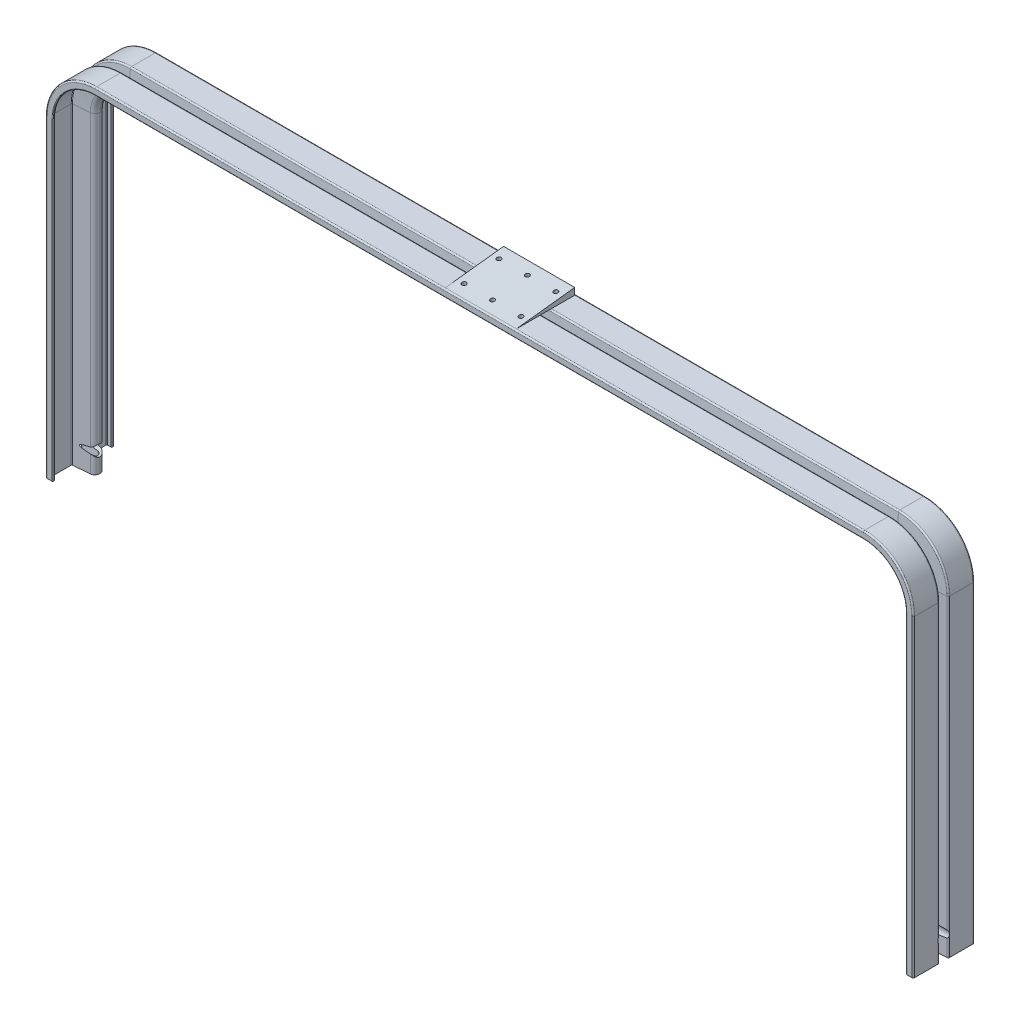
SolidWorks part; units mm, degrees
material "AISI 1020 Acero laminado en frío"
ref_plane "Alzado" through (0, 0, 0) normal (0, 0, 1) x (1, 0, 0)
ref_plane "Planta" through (0, 0, 0) normal (0, 1, 0) x (1, 0, 0)
ref_plane "Vista lateral" through (0, 0, 0) normal (1, 0, 0) x (0, 0, -1)
other "Tabla de configuración"
sketch "Croquis2" plane through (0, 0, 0) normal (1, 0, 0) x (0, 0, -1)
  line L4 (2, -2) -> (-2, -2) construction
  line L5 (21.5, 12) -> (-21.5, 12) construction
  line L8 (-3.5977, -0.2791) -> (-2.1024, -0.1595) construction
  line L9 (0, -3.5) -> (0, 12) construction
  line L10 (-3.0048, 11.1196) -> (-2.9952, 11)
  line L11 (-5.8278, 10.3021) -> (-7.826, 10.3021) construction
  line L12 (-5.8278, 10.3021) -> (-5.8278, 13.2411) construction
  line L13 (-5.8278, 13.2411) -> (-20.5, 13.2411)
  line L14 (-21.5, 12.2411) -> (-21.5, 8.7411)
  line L15 (-21, 8.2411) -> (-20.5, 8.2411)
  line L16 (-20, 8.7411) -> (-20, 11.2411)
  line L17 (-19.5, 11.7411) -> (-5.8278, 11.7411)
  line L18 (-4.5, 11) -> (-4.9298, 10.9656) construction
  line L19 (-4.5, 11) -> (-4.5881, 12.1007) construction
  line L20 (-5.8278, 11.7411) -> (-4.3336, 11.7411) construction
  line L21 (-4.5, 11) -> (-4.5225, 11.281)
  line L22 (-5.0209, 11.7411) -> (-5.8278, 11.7411)
  line L23 (-2.9952, 11) -> (-3.0048, 11.1196)
  line L24 (-3.0048, 11.1196) -> (-3.1009, 12.3209)
  line L25 (-5.8278, 13.2411) -> (-4.0977, 13.2411)
  line L26 (0.1088, -3.5) -> (-0.1088, -3.5)
  line L27 (-3.5977, -0.2791) -> (-4.5, 11)
  line L28 (-1.2335, -2) -> (-1.103, -2.2764) construction
  line L29 (-2.5488, 5.4203) -> (-1.7472, -4.6) construction
  line L30 (-1.236, -2) -> (-1.2335, -2)
  line L31 (-2.1024, -0.1595) -> (-2.9952, 11)
  line L32 (0.1088, -2) -> (-0.1088, -2)
  line L33 (-2.1024, -0.1595) -> (-2.9952, 11)
  line L34 (2.5488, 5.4203) -> (1.7472, -4.6) construction
  line L35 (1.2335, -2) -> (1.103, -2.2764) construction
  line L36 (5.8278, 11.7411) -> (4.3336, 11.7411) construction
  line L37 (4.5, 11) -> (4.5881, 12.1007) construction
  line L38 (4.5, 11) -> (4.9298, 10.9656) construction
  line L39 (5.8278, 10.3021) -> (5.8278, 13.2411) construction
  line L40 (5.8278, 10.3021) -> (7.826, 10.3021) construction
  line L41 (3.5977, -0.2791) -> (2.1024, -0.1595) construction
  line L42 (2.1024, -0.1595) -> (2.9952, 11)
  line L43 (2.1024, -0.1595) -> (2.9952, 11)
  line L44 (1.236, -2) -> (1.2335, -2)
  line L45 (3.5977, -0.2791) -> (4.5, 11)
  line L46 (5.8278, 13.2411) -> (4.0977, 13.2411)
  line L47 (3.0048, 11.1196) -> (3.1009, 12.3209)
  line L48 (2.9952, 11) -> (3.0048, 11.1196)
  line L49 (5.0209, 11.7411) -> (5.8278, 11.7411)
  line L50 (4.5, 11) -> (4.5225, 11.281)
  line L51 (19.5, 11.7411) -> (5.8278, 11.7411)
  line L52 (20, 8.7411) -> (20, 11.2411)
  line L53 (21, 8.2411) -> (20.5, 8.2411)
  line L54 (21.5, 12.2411) -> (21.5, 8.7411)
  line L55 (5.8278, 13.2411) -> (20.5, 13.2411)
  line L56 (3.0048, 11.1196) -> (2.9952, 11)
  arc A0 (-2.1024, -0.1595) -> (-0.1088, -2) centre (-0.1088, 0) ccw
  arc A1 (3.5977, -0.2791) -> (0.1088, -3.5) centre (0.1088, 0) cw
  arc A4 (-5.0209, 11.7411) -> (-4.5225, 11.281) centre (-5.0209, 11.2411) cw
  arc A5 (-3.1009, 12.3209) -> (-4.0977, 13.2411) centre (-4.0977, 12.2411) ccw
  arc A6 (-20, 11.2411) -> (-19.5, 11.7411) centre (-19.5, 11.2411) cw
  arc A7 (-20.5, 13.2411) -> (-21.5, 12.2411) centre (-20.5, 12.2411) ccw
  arc A8 (-20, 8.7411) -> (-20.5, 8.2411) centre (-20.5, 8.7411) cw
  arc A9 (-21, 8.2411) -> (-21.5, 8.7411) centre (-21, 8.7411) cw
  arc A10 (-3.5977, -0.2791) -> (-0.1088, -3.5) centre (-0.1088, 0) ccw
  arc A11 (21, 8.2411) -> (21.5, 8.7411) centre (21, 8.7411) ccw
  arc A12 (20, 8.7411) -> (20.5, 8.2411) centre (20.5, 8.7411) ccw
  arc A13 (20.5, 13.2411) -> (21.5, 12.2411) centre (20.5, 12.2411) cw
  arc A14 (20, 11.2411) -> (19.5, 11.7411) centre (19.5, 11.2411) ccw
  arc A15 (3.1009, 12.3209) -> (4.0977, 13.2411) centre (4.0977, 12.2411) cw
  arc A16 (5.0209, 11.7411) -> (4.5225, 11.281) centre (5.0209, 11.2411) ccw
  arc A17 (2.1024, -0.1595) -> (0.1088, -2) centre (0.1088, 0) cw
  point P4 (0, 0)
  point P8 (0, 12)
  point P32 (-4.5593, 11.7411)
  point P49 (-1.9552, -2)
  point P88 (0, -2)
  point P90 (1.9552, -2)
  point P91 (4.5593, 11.7411)
  dimension "D3" = 3.5
  dimension "D8" = 1.5
  dimension "D9" = 0.5
  dimension "D11" = 1
  dimension "D12" = 1.361
  dimension "D13" = 0.5
  dimension "D14" = 1
  dimension "D15" = 0.5
  dimension "D5" = 2
  dimension "D6" = 2
  dimension "D10" = 1.5
  dimension "D16" = 21.5
extrude "Saliente-Extruir1" add sketch "Croquis2" along normal mid plane 540
sketch "Croquis4" plane through (0, 0, 0) normal (0, 0, 1) x (1, 0, 0)
  line L0 (0, -4.7328) -> (0, 13.2411) construction
  line L1 (270, 13.2411) -> (-270, 13.2411) construction
  line L2 (0, 115.1283) -> (-251.0425, 15.746)
  line L3 (-270, -12.1478) -> (-270, -232.1463)
  line L4 (270, -12.1478) -> (270, -232.1463)
  line L5 (0, 115.1283) -> (251.0425, 15.746)
  arc A0 (-251.0425, 15.746) -> (-270, -12.1478) centre (-240, -12.1478) ccw
  arc A1 (251.0425, 15.746) -> (270, -12.1478) centre (240, -12.1478) cw
  point P10 (-270, 8.2411)
  point P15 (270, 8.2411)
  dimension "D1" = 30
  dimension "D2" = 269.9985
  dimension "D3" = 219.9985
sketch "Croquis9" plane through (270, 0, 0) normal (1, 0, 0) x (0, 0, -1)
  line L0 (-19.5, 11.7411) -> (-5.0209, 11.7411)
  line L1 (-4.5225, 11.281) -> (-3.5977, -0.2791)
  line L2 (-3.1009, 12.3209) -> (-2.1024, -0.1595)
  line L3 (2.1024, -0.1595) -> (3.1009, 12.3209)
  line L4 (4.5225, 11.281) -> (3.5977, -0.2791)
  line L5 (4.0977, 13.2411) -> (20.5, 13.2411)
  line L6 (21.5, 12.2411) -> (21.5, 8.7411)
  line L7 (21, 8.2411) -> (20.5, 8.2411)
  line L8 (21, 8.2411) -> (20.5, 8.2411) construction
  line L9 (20, 8.7411) -> (20, 11.2411)
  line L10 (19.5, 11.7411) -> (5.0209, 11.7411)
  line L11 (-20, 11.2411) -> (-20, 8.7411)
  line L12 (-20.5, 8.2411) -> (-21, 8.2411)
  line L13 (-21.5, 8.7411) -> (-21.5, 12.2411)
  line L14 (-20.5, 13.2411) -> (-4.0977, 13.2411)
  line L15 (-0.1088, -2) -> (0.1088, -2)
  line L16 (-0.1088, -3.5) -> (0.1088, -3.5)
  line L17 (-0.1088, -21.7589) -> (18.9384, -21.7589) construction
  arc A0 (21, 8.2411) -> (21.5, 8.7411) centre (21, 8.7411) ccw construction
  arc A1 (-21, 8.2411) -> (-21.5, 8.7411) centre (-21, 8.7411) cw
  arc A2 (-21.5, 12.2411) -> (-20.5, 13.2411) centre (-20.5, 12.2411) cw
  arc A3 (-20, 11.2411) -> (-19.5, 11.7411) centre (-19.5, 11.2411) cw
  arc A4 (-5.0209, 11.7411) -> (-4.5225, 11.281) centre (-5.0209, 11.2411) cw
  arc A5 (-4.0977, 13.2411) -> (-3.1009, 12.3209) centre (-4.0977, 12.2411) cw
  arc A6 (-3.5977, -0.2791) -> (-0.1088, -3.5) centre (-0.1088, 0) ccw
  arc A7 (-2.1024, -0.1595) -> (-0.1088, -2) centre (-0.1088, 0) ccw
  arc A8 (2.1024, -0.1595) -> (0.1088, -2) centre (0.1088, 0) cw
  arc A9 (3.5977, -0.2791) -> (0.1088, -3.5) centre (0.1088, 0) cw
  arc A10 (3.1009, 12.3209) -> (4.0977, 13.2411) centre (4.0977, 12.2411) cw
  arc A11 (4.5225, 11.281) -> (5.0209, 11.7411) centre (5.0209, 11.2411) cw
  arc A12 (19.5, 11.7411) -> (20, 11.2411) centre (19.5, 11.2411) cw
  arc A13 (20.5, 13.2411) -> (21.5, 12.2411) centre (20.5, 12.2411) cw
  arc A14 (20, 8.7411) -> (20.5, 8.2411) centre (20.5, 8.7411) ccw
  arc A15 (21, 8.2411) -> (21.5, 8.7411) centre (21, 8.7411) ccw
  arc A16 (-20.5, 8.2411) -> (-20, 8.7411) centre (-20.5, 8.7411) ccw
  dimension "D1" = 30
revolve "Revolución1" add sketch "Croquis9" angle 90 about L17
mirror "Simetría1" about plane through (0, 0, 0) normal (1, 0, 0) of "Revolución1"
sketch "Croquis10" plane through (0, -21.7589, 0) normal (0, -1, 0) x (1, 0, 0)
  line L0 (300.5, 21.5) -> (304, 21.5)
  line L1 (305, 20.5) -> (305, 4.0977)
  line L2 (300, 20.5) -> (300, 21)
  line L3 (300.5, 20) -> (303, 20)
  line L4 (303.5, 19.5) -> (303.5, 5.0209)
  line L5 (303.0399, 4.5225) -> (291.4798, 3.5977)
  line L6 (304.0797, 3.1009) -> (291.5994, 2.1024)
  line L7 (288.2589, -0.1088) -> (288.2589, 0.1088)
  line L8 (289.7589, -0.1088) -> (289.7589, 0.1088)
  line L9 (291.5994, -2.1024) -> (304.0797, -3.1009)
  line L10 (291.4798, -3.5977) -> (303.0399, -4.5225)
  line L11 (303.5, -19.5) -> (303.5, -5.0209)
  line L12 (305, -4.0977) -> (305, -20.5)
  line L13 (303, -20) -> (300.5, -20)
  line L14 (304, -21.5) -> (300.5, -21.5)
  line L15 (300, -21) -> (300, -20.5)
  arc A0 (304, 21.5) -> (305, 20.5) centre (304, 20.5) cw
  arc A1 (300.5, 21.5) -> (300, 21) centre (300.5, 21) ccw
  arc A2 (300, 20.5) -> (300.5, 20) centre (300.5, 20.5) ccw
  arc A3 (303, 20) -> (303.5, 19.5) centre (303, 19.5) cw
  arc A4 (303.5, 5.0209) -> (303.0399, 4.5225) centre (303, 5.0209) cw
  arc A5 (305, 4.0977) -> (304.0797, 3.1009) centre (304, 4.0977) cw
  arc A6 (291.4798, 3.5977) -> (288.2589, 0.1088) centre (291.7589, 0.1088) ccw
  arc A7 (291.5994, 2.1024) -> (289.7589, 0.1088) centre (291.7589, 0.1088) ccw
  arc A8 (288.2589, -0.1088) -> (291.4798, -3.5977) centre (291.7589, -0.1088) ccw
  arc A9 (289.7589, -0.1088) -> (291.5994, -2.1024) centre (291.7589, -0.1088) ccw
  arc A10 (303.5, -5.0209) -> (303.0399, -4.5225) centre (303, -5.0209) ccw
  arc A11 (304.0797, -3.1009) -> (305, -4.0977) centre (304, -4.0977) cw
  arc A12 (305, -20.5) -> (304, -21.5) centre (304, -20.5) cw
  arc A13 (303, -20) -> (303.5, -19.5) centre (303, -19.5) ccw
  arc A14 (300.5, -21.5) -> (300, -21) centre (300.5, -21) cw
  arc A15 (300, -20.5) -> (300.5, -20) centre (300.5, -20.5) cw
extrude "Saliente-Extruir2" add sketch "Croquis10" along normal blind 220
mirror "Simetría2" about plane through (0, 0, 0) normal (1, 0, 0) of "Saliente-Extruir2"
sketch "Croquis11" plane through (-305, 0, 0) normal (-1, 0, 0) x (0, 0, 1)
  line L0 (0.1088, -241.7589) -> (0.1088, -21.7589) construction
  circle A0 centre (0.1088, -227.4294) radius 4.05
  dimension "D1" = 8.1
extrude "Cortar-Extruir1" cut sketch "Croquis11" against normal through all
sketch "Croquis12" plane through (0, 0, 0) normal (1, 0, 0) x (0, 0, -1)
  line L0 (20.5, 13.2411) -> (20.5, 17.985)
  line L1 (20.5, 17.985) -> (-20.5, 13.2411)
  line L2 (-20.5, 13.2411) -> (20.5, 13.2411)
  line L3 (4.0977, 13.2411) -> (20.5, 13.2411) construction
  line L4 (20.5, -21.7589) -> (20.5, 13.2411) construction
  line L5 (-20.5, -21.7589) -> (-20.5, 13.2411) construction
  point P5 (20.3725, 18.2164)
  point P6 (20.5, 15.6131)
  dimension "D3" = 41
  dimension "D4" = 6.6
extrude "Saliente-Extruir3" add sketch "Croquis12" along normal mid plane 50
sketch "Croquis13" plane through (0, 11.7411, 0) normal (0, -1, 0) x (1, 0, 0)
  line L1 (270, 19.5) -> (-270, 19.5) construction
  line L2 (0, 0) -> (0, 24.52) construction
  line L3 (0, -23.65) -> (0, 23.65) construction
  line L6 (142.8591, 0) -> (-142.8591, 0) construction
  circle A16 centre (0, 12.26) radius 1.5
  circle A17 centre (20, 12.26) radius 1.5
  circle A18 centre (-20, 12.26) radius 1.5
  circle A19 centre (20, -12.26) radius 1.5
  circle A20 centre (0, -12.26) radius 1.5
  circle A21 centre (-20, -12.26) radius 1.5
  dimension "D1" = 7.24
  dimension "D2" = 2
extrude "Cortar-Extruir2" cut sketch "Croquis13" against normal through all
